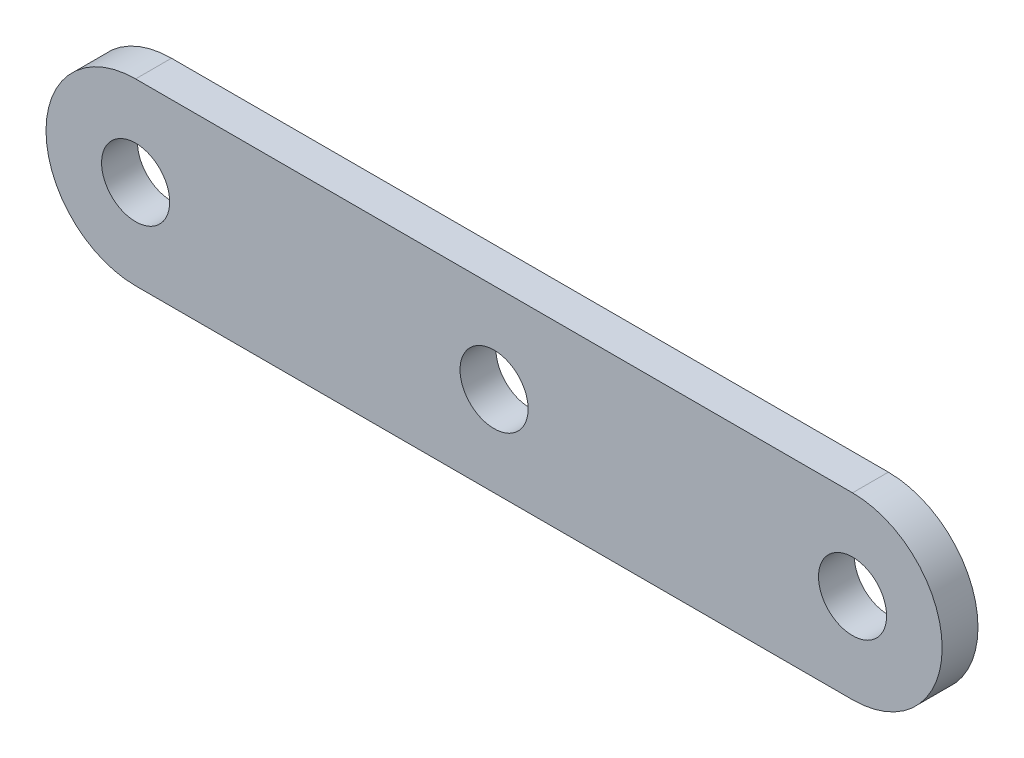
SolidWorks part; units mm, degrees
material "6061 Alloy"
ref_plane "Front Plane" through (0, 0, 0) normal (0, 0, 1) x (1, 0, 0)
ref_plane "Top Plane" through (0, 0, 0) normal (0, 1, 0) x (1, 0, 0)
ref_plane "Right Plane" through (0, 0, 0) normal (1, 0, 0) x (0, 0, -1)
sketch "Croquis1" plane through (0, 0, 0) normal (0, 0, 1) x (1, 0, 0)
  line L0 (-25.4, 7.8587) -> (25.4, -4.8413) construction
  line L1 (25.4, -4.8413) -> (-25.4, -4.8413)
  line L3 (25.4, 7.8587) -> (-25.4, 7.8587)
  arc A0 (-25.4, 7.8587) -> (-25.4, -4.8413) centre (-25.4, 1.5087) ccw
  arc A1 (25.4, -4.8413) -> (25.4, 7.8587) centre (25.4, 1.5087) ccw
  circle A2 centre (-25.4, 1.5087) radius 2.413
  circle A3 centre (0, 1.5087) radius 2.413
  circle A4 centre (25.4, 1.5087) radius 2.413
  point P0 (0, 0)
  dimension "D2" = 6.35
  dimension "D3" = 4.826
  dimension "D1" = 50.8
extrude "Saliente-Extruir1" add sketch "Croquis1" along normal mid plane 2.54
